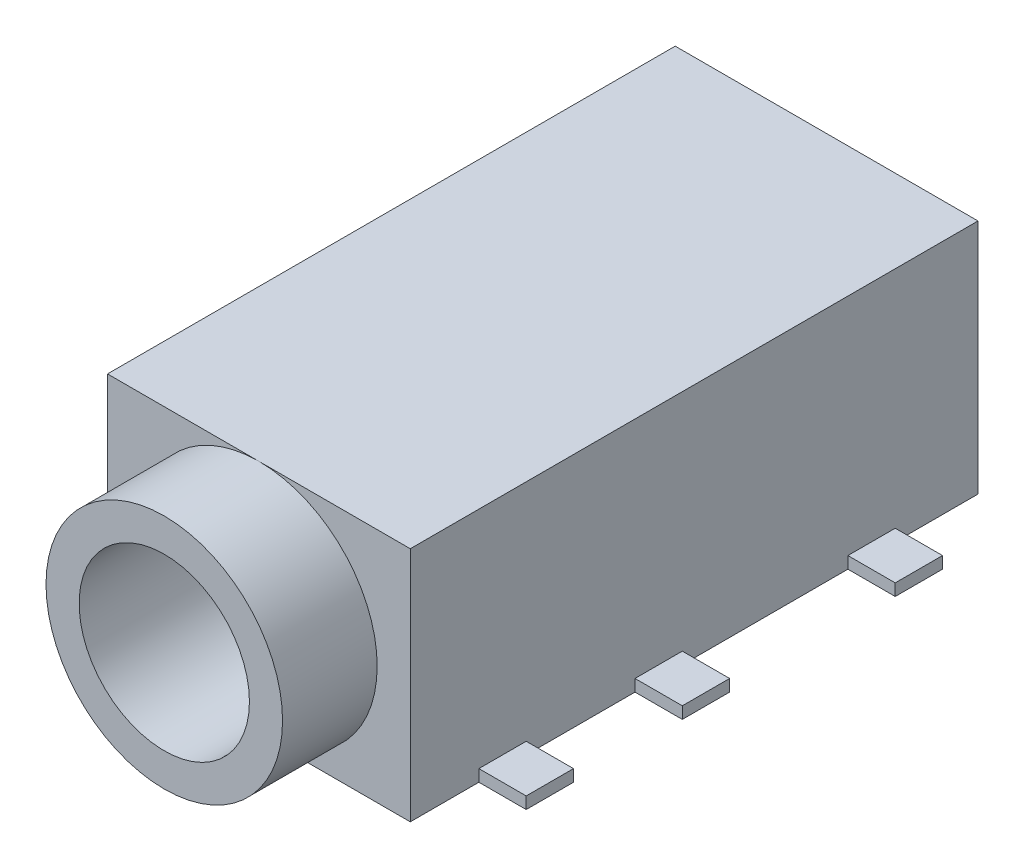
SolidWorks part; units mm, degrees
ref_plane "前视基准面" through (0, 0, 0) normal (0, 0, 1) x (1, 0, 0)
ref_plane "上视基准面" through (0, 0, 0) normal (0, 1, 0) x (1, 0, 0)
ref_plane "右视基准面" through (0, 0, 0) normal (1, 0, 0) x (0, 0, -1)
sketch "草图1" plane through (0, 0, 0) normal (0, 1, 0) x (1, 0, 0)
  line L1 (-3.2, 0) -> (3.2, 0)
  line L2 (-3.2, 0) -> (-3.2, 12)
  line L3 (-3.2, 12) -> (3.2, 12)
  line L4 (3.2, 0) -> (3.2, 12)
  line L5 (-3.2, 0) -> (3.2, 12) construction
  line L6 (-3.2, 12) -> (3.2, 0) construction
  point P0 (0, 6)
  point P7 (0, 0)
  dimension "D1" = 6.4
  dimension "D2" = 12
extrude "凸台-拉伸1" add sketch "草图1" along normal blind 5
sketch "草图2" plane through (0, 0, 0) normal (0, 0, 1) x (1, 0, 0)
  line L0 (-3.2, 5) -> (3.2, 0) construction
  line L1 (-3.2, 0) -> (3.2, 5) construction
  circle A0 centre (0, 2.5) radius 2.5
  point P13 (0, 2.5)
extrude "凸台-拉伸2" add sketch "草图2" along normal blind 2
sketch "草图3" plane through (0, 0, 0) normal (0, -1, 0) x (1, 0, 0)
  line L0 (0, 0) -> (0, -3) construction
  line L1 (0, -3) -> (0, -9) construction
  circle A0 centre (0, -3) radius 0.8
  circle A1 centre (0, -9) radius 0.8
  dimension "D3" = 1.6
  dimension "D1" = 3
  dimension "D2" = 6
extrude "凸台-拉伸3" add sketch "草图3" along normal blind 0.5
sketch "草图4" plane through (3.2, 0, 0) normal (1, 0, 0) x (0, 0, -1)
  line L0 (0, 0) -> (12, 0) construction
  line L1 (1.45, 0) -> (2.45, 0)
  line L2 (1.45, 0) -> (1.45, 0.25)
  line L3 (1.45, 0.25) -> (2.45, 0.25)
  line L4 (2.45, 0) -> (2.45, 0.25)
  line L5 (0, 5) -> (0, 0) construction
  line L6 (4.75, 0) -> (5.75, 0)
  line L7 (4.75, 0) -> (4.75, 0.25)
  line L8 (4.75, 0.25) -> (5.75, 0.25)
  line L9 (5.75, 0) -> (5.75, 0.25)
  line L10 (9.25, 0) -> (10.25, 0)
  line L11 (9.25, 0) -> (9.25, 0.25)
  line L12 (9.25, 0.25) -> (10.25, 0.25)
  line L13 (10.25, 0) -> (10.25, 0.25)
  point P14 (1.95, 0)
  point P16 (5.25, 0)
  point P17 (9.75, 0)
  dimension "D1" = 1
  dimension "D2" = 1.95
  dimension "D3" = 5.25
  dimension "D4" = 9.75
  dimension "D5" = 0.25
extrude "凸台-拉伸4" add sketch "草图4" along normal blind 1
sketch "草图5" plane through (0, 0, 2) normal (0, 0, 1) x (1, 0, 0)
  circle A0 centre (0, 2.5) radius 1.8
  dimension "D1" = 3.6
extrude "切除-拉伸1" cut sketch "草图5" against normal through all
sketch "草图6" plane through (-3.2, 0, 0) normal (-1, 0, 0) x (0, 0, 1)
  line L0 (-12, 0) -> (0, 0) construction
  line L1 (-2, 0) -> (-3, 0)
  line L2 (-2, 0) -> (-2, 0.25)
  line L3 (-2, 0.25) -> (-3, 0.25)
  line L4 (-3, 0) -> (-3, 0.25)
  line L5 (0, 5) -> (0, 0) construction
  line L6 (0, 0) -> (0, 5) construction
  line L7 (-7, 0) -> (-8, 0)
  line L8 (-7, 0) -> (-7, 0.25)
  line L9 (-7, 0.25) -> (-8, 0.25)
  line L10 (-8, 0) -> (-8, 0.25)
  point P6 (-2.5, 0)
  point P13 (-7.5, 0)
  dimension "D1" = 1
  dimension "D2" = 0.25
  dimension "D3" = 2.5
  dimension "D4" = 7.5
extrude "凸台-拉伸5" add sketch "草图6" along normal blind 1
